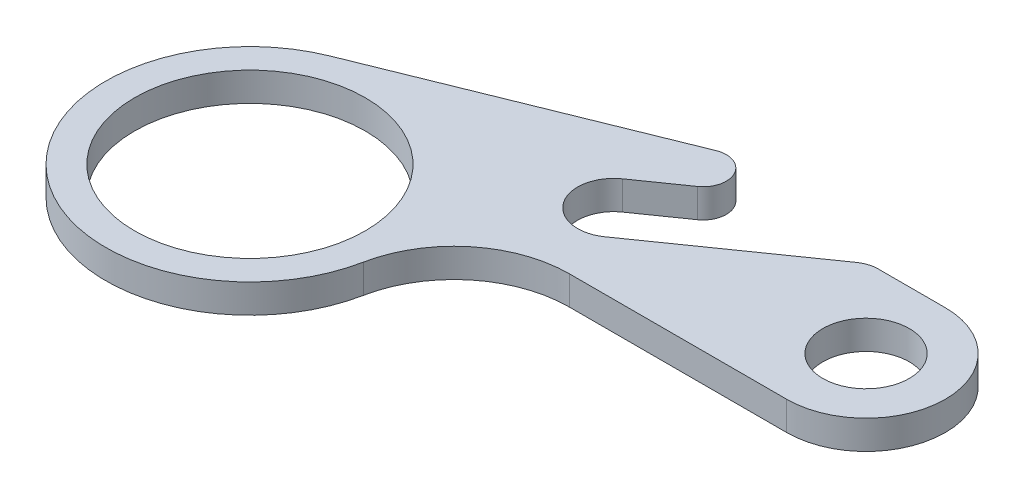
SolidWorks part; units mm, degrees
material "303 SS"
ref_plane "Front Plane" through (0, 0, 0) normal (0, 0, 1) x (1, 0, 0)
ref_plane "Top Plane" through (0, 0, 0) normal (0, 1, 0) x (1, 0, 0)
ref_plane "Right Plane" through (0, 0, 0) normal (1, 0, 0) x (0, 0, -1)
sketch "Sketch1" plane through (0, 0, 0) normal (0, 1, 0) x (1, 0, 0)
  line L0 (0, 0) -> (-31.75, 0) construction
  line L1 (0, -8.7312) -> (-23.926, -8.7312)
  line L2 (0, 8.7313) -> (-7.3914, 8.7312)
  line L3 (-27.7813, 0) -> (-15.3117, 8.7312) construction
  line L4 (-30.0576, 3.251) -> (-25.2025, 6.6506)
  line L5 (-25.5049, -3.251) -> (-9.2125, 8.1571)
  line L7 (-57.904, -1.1566) -> (-27.6111, 11.0862)
  arc A0 (0, -8.7312) -> (0, 8.7313) centre (0, 0) ccw
  circle A2 centre (0, 0) radius 4.7625
  arc A3 (-30.0576, 3.251) -> (-25.5049, -3.251) centre (-27.7813, 0) ccw
  arc A4 (-57.904, -1.1566) -> (-36.3836, -18.9618) centre (-51.9556, -15.875) ccw
  circle A5 centre (-51.9556, -15.875) radius 12.7
  arc A7 (-27.6111, 11.0862) -> (-25.2025, 6.6506) centre (-26.6594, 8.7313) cw
  arc A8 (-9.2125, 8.1571) -> (-7.3914, 8.7312) centre (-7.3914, 5.5563) cw
  arc A9 (-36.3836, -18.9618) -> (-23.926, -8.7312) centre (-23.926, -21.4312) cw
  point P21 (-22.231, 8.7312)
  point P27 (-8.3924, 8.7312)
  dimension "D3" = 9.525
  dimension "D7" = 31.75
  dimension "D8" = 25.4
  dimension "D9" = 51.9556
  dimension "D2" = 2.54
  dimension "D10" = 3.175
  dimension "D11" = 12.7
  dimension "D1" = 17.4625
  dimension "D4" = 7.9375
  dimension "D5" = 27.7813
  dimension "D6" = 35
  dimension "D12" = 17.4625
  dimension "D13" = 15.875
extrude "Boss-Extrude1" add sketch "Sketch1" along normal blind 3.175
scale "Scale1" scale about centroid uniform scaling yes scale factor 0.6
